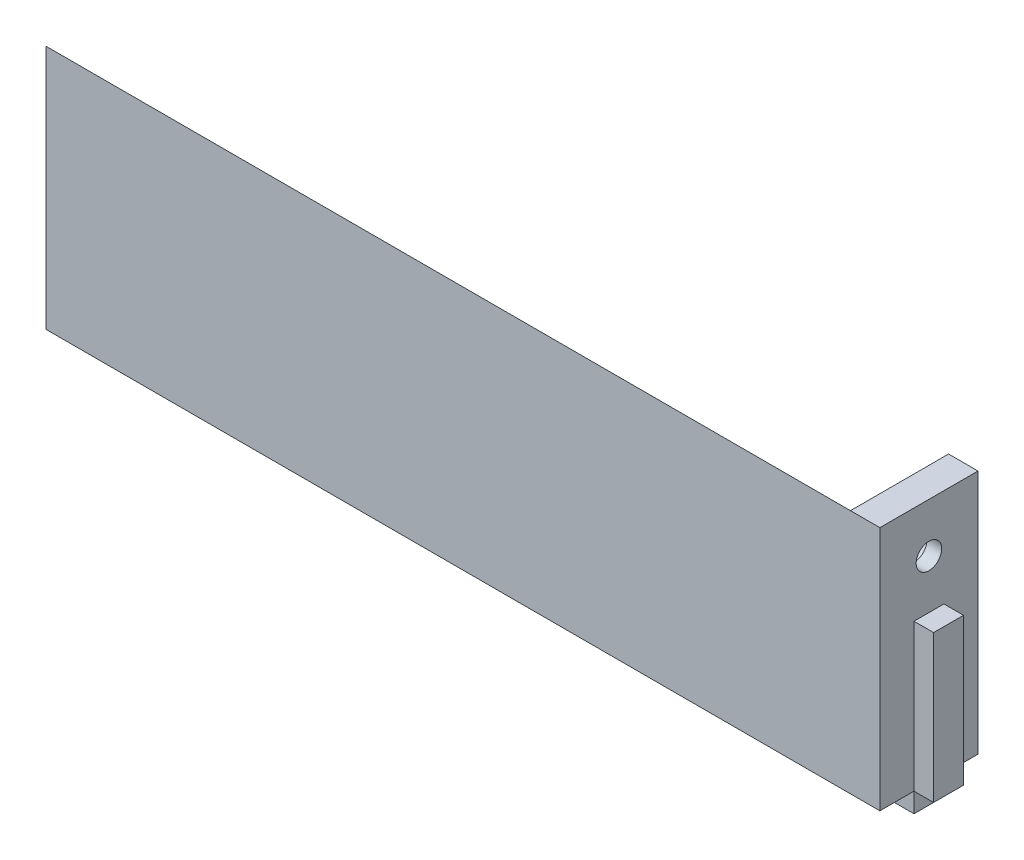
SolidWorks part; units mm, degrees
ref_plane "前视基准面" through (0, 0, 0) normal (0, 0, 1) x (1, 0, 0)
ref_plane "上视基准面" through (0, 0, 0) normal (0, 1, 0) x (1, 0, 0)
ref_plane "右视基准面" through (0, 0, 0) normal (1, 0, 0) x (0, 0, -1)
other "Configuration Table"
sketch "草图1" plane through (0, 0, 0) normal (0, 1, 0) x (1, 0, 0)
  line L1 (0, 0) -> (170, 0)
  line L2 (0, 0) -> (0, 20)
  line L3 (0, 20) -> (170, 20)
  line L4 (170, 0) -> (170, 20)
extrude "凸台-拉伸1" add sketch "草图1" along normal blind 50
sketch "草图2" plane through (170, 0, 0) normal (1, 0, 0) x (0, 0, -1)
  line L0 (0, 50) -> (20, 0)
  line L1 (20, 0) -> (20, 50)
  line L2 (20, 50) -> (0, 50)
extrude "切除-拉伸2" cut sketch "草图2" against normal blind 164
sketch "草图3" plane through (6, 0, 0) normal (1, 0, 0) x (0, 0, -1)
  line L0 (10, 50) -> (10, 40)
  line L1 (20, 50) -> (0, 50) construction
  circle A0 centre (10, 40) radius 5
extrude "切除-拉伸3" cut sketch "草图3" against normal blind 3
sketch "草图4" plane through (3, 0, 0) normal (1, 0, 0) x (0, 0, -1)
  circle A0 centre (10, 40) radius 2.6
extrude "切除-拉伸4" cut sketch "草图4" against normal blind 3
mirror "镜向1" about plane through (170, 50, 0) normal (-1, 0, 0) of "凸台-拉伸1", "切除-拉伸2", "切除-拉伸3", "切除-拉伸4"
sketch "草图5" plane through (0, 0, 0) normal (0, -1, 0) x (1, 0, 0)
  line L0 (334, -20) -> (6, -20) construction
  line L1 (0, 0) -> (170, 0)
  line L2 (0, 0) -> (0, -20)
  line L3 (0, -20) -> (170, -20)
  line L4 (170, 0) -> (170, -20)
extrude "切除-拉伸5" cut sketch "草图5" against normal blind 400
sketch "草图6" plane through (0, 0, 0) normal (0, -1, 0) x (1, 0, 0)
  line L0 (170, -10) -> (231.37, -10)
  line L1 (170, -20) -> (170, 0) construction
  circle A0 centre (231.37, -10) radius 5
extrude "切除-拉伸6" cut sketch "草图6" against normal blind 400
sketch "草图7" plane through (0, 0, 0) normal (0, -1, 0) x (1, 0, 0)
  circle A0 centre (231.37, -10) radius 5
  circle A1 centre (231.37, -10) radius 2.6
extrude "凸台-拉伸2" add sketch "草图7" against normal blind 3
sketch "草图8" plane through (0, 0, 0) normal (0, -1, 0) x (1, 0, 0)
  line L0 (340, -10) -> (340, -6.95)
  line L1 (340, -20) -> (340, 0) construction
  line L2 (340, -10) -> (260, -10)
  line L3 (260, -10) -> (260, -13.05)
  line L4 (170, -10) -> (170, -6.95)
  line L5 (260, -13.05) -> (340, -13.05)
  line L6 (260, -13.05) -> (260, -6.95)
  line L7 (260, -6.95) -> (340, -6.95)
  line L8 (340, -13.05) -> (340, -6.95)
  line L9 (170, -20) -> (170, 0) construction
  line L10 (170, -10) -> (205, -10)
  line L11 (205, -10) -> (205, -13.05)
  line L13 (170, -6.95) -> (205, -6.95)
  line L14 (170, -6.95) -> (170, -13.05)
  line L15 (170, -13.05) -> (205, -13.05)
  line L16 (205, -6.95) -> (205, -13.05)
  line M7 (170, 0) -> (170, -20)
  line M10 (340, -20) -> (340, 0)
extrude "凸台-拉伸3" add sketch "草图8" along normal blind 4 contours L16 L13 L10 M7 | L15 L11 L10 M7 | L7 L6 L2 M10 | L3 L5 L2 M10
sketch "草图9" plane through (340, 0, 0) normal (1, 0, 0) x (0, 0, -1)
  line L5 (13.05, 0) -> (6.95, 0)
  line L6 (13.05, 0) -> (13.05, 30)
  line L7 (13.05, 30) -> (6.95, 30)
  line L8 (6.95, 0) -> (6.95, 30)
extrude "凸台-拉伸4" add sketch "草图9" along normal blind 4
